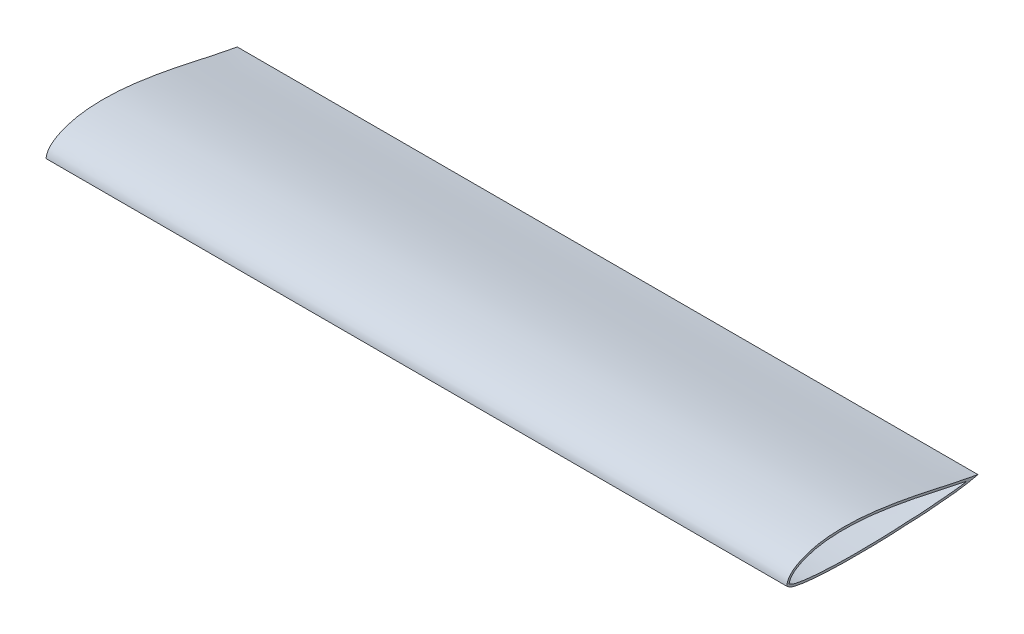
SolidWorks part; units mm, degrees
ref_plane "Спереди" through (0, 0, 0) normal (0, 0, 1) x (1, 0, 0)
ref_plane "Сверху" through (0, 0, 0) normal (0, 1, 0) x (1, 0, 0)
ref_plane "Справа" through (0, 0, 0) normal (1, 0, 0) x (0, 0, -1)
sketch "Эскиз1" plane through (0, 0, 0) normal (1, 0, 0) x (0, 0, -1)
  spline S0 degree 3 poles (-240, 0) (-238.5396, 6.886) (-231.612, 12.3378) (-222.1753, 17.4121) (-214.1119, 20.3435) (-204.1561, 23.2639) (-188.1046, 25.8933) (-168.0072, 26.9601) (-143.9456, 26.0264) (-119.9183, 23.5678) (-95.9538, 19.7588) (-71.9127, 15.562) (-48.006, 10.2206) (-23.9898, 5.1714) (-8.0375, 1.5236) (0, 0) knots 0 0 0 0 0.075346 0.102328 0.12789 0.177564 0.226025 0.321727 0.4173 0.513305 0.60992 0.706974 0.804635 0.902346 1 1 1 1
  spline S1 degree 3 poles (-240, 0) (-236.5239, -2.8866) (-230.2208, -4.0678) (-222.0286, -5.6488) (-214.0096, -6.6085) (-204.0195, -7.6506) (-188.0105, -8.621) (-168.0084, -9.355) (-143.9974, -9.5447) (-119.9964, -9.0006) (-95.9841, -8.4523) (-79.4445, -6.8615) (-63.4129, -6.9414) (-47.4215, -5.1493) (-23.952, -3.3462) (-7.916, -1.6722) (0, 0) knots 0 0 0 0 0.053475 0.078709 0.103753 0.153673 0.203448 0.302856 0.402199 0.501554 0.600955 0.70043 0.70748 0.799996 0.899716 1 1 1 1
  spline S2 degree 1 poles (-243.3107, -1.1503) (15.2682, 0.1592) knots 0 0 1 1 construction
  spline S3 degree 1 poles (-243.3107, -1.1503) (15.2682, 0.1592) knots 0 0 1 1 construction
  spline S4 degree 3 poles (-243.3107, -1.1503) (-243.23, -0.7697) (-243.1053, -0.1854) (-242.9535, 0.5399) (-242.7534, 1.4447) (-242.4561, 2.5031) (-241.8803, 4.1474) (-240.9865, 6.0591) (-239.2406, 8.8308) (-236.588, 11.7648) (-232.9731, 14.6121) (-229.2224, 16.9699) (-225.3956, 19.0964) (-221.3077, 20.9247) (-217.2278, 22.38) (-213.1726, 23.7014) (-207.6753, 25.3023) (-200.6627, 26.9042) (-192.1979, 28.1735) (-180.902, 29.3008) (-166.7519, 29.7752) (-149.8461, 29.2809) (-133.0218, 27.977) (-116.2679, 25.9821) (-99.6531, 23.3815) (-83.1194, 20.5935) (-66.5699, 17.4231) (-50.1969, 13.7991) (-36.581, 10.889) (-25.6533, 8.5412) (-17.466, 6.7288) (-9.3086, 4.9303) (-1.1842, 3.2552) (7.0427, 1.7249) (12.5263, 0.6789) (15.2682, 0.1592) knots -0.006466 -0.006466 -0.006466 -0.006466 -0.002301 -0.000219 0.001863 0.006027 0.010191 0.01852 0.026848 0.043505 0.060162 0.076819 0.093476 0.110132 0.126789 0.143446 0.160103 0.193417 0.22673 0.260044 0.326671 0.393299 0.459926 0.526553 0.593181 0.659808 0.726435 0.793063 0.85969 0.893004 0.926318 0.959631 0.992945 1.026259 1.059572 1.059572 1.059572 1.059572
  spline S5 degree 3 poles (15.2682, 0.1592) (12.6312, -0.3979) (8.6789, -1.2328) (4.057, -2.2092) (1.4314, -2.7638) (-1.2522, -3.3308) (-4.6476, -3.9518) (-10.0619, -4.7892) (-16.8341, -5.5946) (-24.9154, -6.3443) (-32.9647, -7.0319) (-41.0025, -7.7071) (-48.9977, -8.437) (-55.7174, -9.1134) (-61.1515, -9.552) (-65.2543, -9.7951) (-68.6964, -9.904) (-71.4669, -9.9009) (-74.0686, -9.9095) (-77.3785, -10.0018) (-82.6758, -10.2591) (-89.3533, -10.7302) (-97.4733, -11.2832) (-105.5981, -11.6304) (-116.396, -11.9329) (-129.8347, -12.232) (-146.0305, -12.4942) (-162.236, -12.4001) (-175.7308, -12.0652) (-186.5267, -11.632) (-194.6147, -11.2271) (-202.7349, -10.7136) (-209.5039, -10.0935) (-214.8897, -9.5081) (-218.9172, -9.0514) (-223.0515, -8.4836) (-226.4356, -7.854) (-229.0691, -7.3508) (-231.108, -6.9556) (-233.2049, -6.4818) (-235.3369, -5.8736) (-237.4805, -5.0674) (-239.2497, -4.1742) (-240.4547, -3.4091) (-241.1345, -2.9251) (-241.5444, -2.6118) (-241.8889, -2.3317) (-242.1551, -2.1094) (-242.6335, -1.713) (-243.0392, -1.3757) (-243.3107, -1.1503) knots -0.007149 -0.007149 -0.007149 -0.007149 0.026258 0.042961 0.051312 0.059664 0.076367 0.09307 0.126477 0.159883 0.19329 0.226696 0.260103 0.293509 0.310212 0.326915 0.343619 0.35197 0.360322 0.377025 0.393728 0.427135 0.460541 0.493948 0.527354 0.594167 0.66098 0.727793 0.794605 0.828012 0.861418 0.894825 0.928231 0.944934 0.961637 0.978341 0.995044 1.003395 1.011747 1.020099 1.02845 1.036802 1.045154 1.049329 1.051417 1.053505 1.054549 1.055593 1.057681 1.061857 1.061857 1.061857 1.061857
  point P0 (-240, 0)
  point P1 (-234, 9.888)
  point P2 (-228, 14.16)
  point P3 (-222, 17.316)
  point P4 (-216, 19.608)
  point P5 (-204, 23.04)
  point P6 (-192, 25.104)
  point P7 (-168, 26.592)
  point P8 (-144, 25.776)
  point P9 (-120, 23.352)
  point P10 (-96, 19.704)
  point P11 (-72, 15.384)
  point P12 (-48, 10.272)
  point P13 (-24, 5.1)
  point P14 (-12, 2.46)
  point P15 (0, 0)
  point P16 (-234, -3.12)
  point P17 (-228, -4.5)
  point P18 (-222, -5.58)
  point P19 (-216, -6.36)
  point P20 (-204, -7.5648)
  point P21 (-192, -8.3472)
  point P22 (-168, -9.24)
  point P23 (-144, -9.4224)
  point P24 (-120, -9)
  point P25 (-96, -8.16)
  point P26 (-72, -6.9024)
  point P27 (-48, -5.34)
  point P28 (-24, -3.24)
  point P29 (-12, -1.98)
  dimension "D1" = 3
extrude "Boss-Extrude1" add sketch "Эскиз1" along normal blind 1000 and the other way blind 1 contours S4 S5
